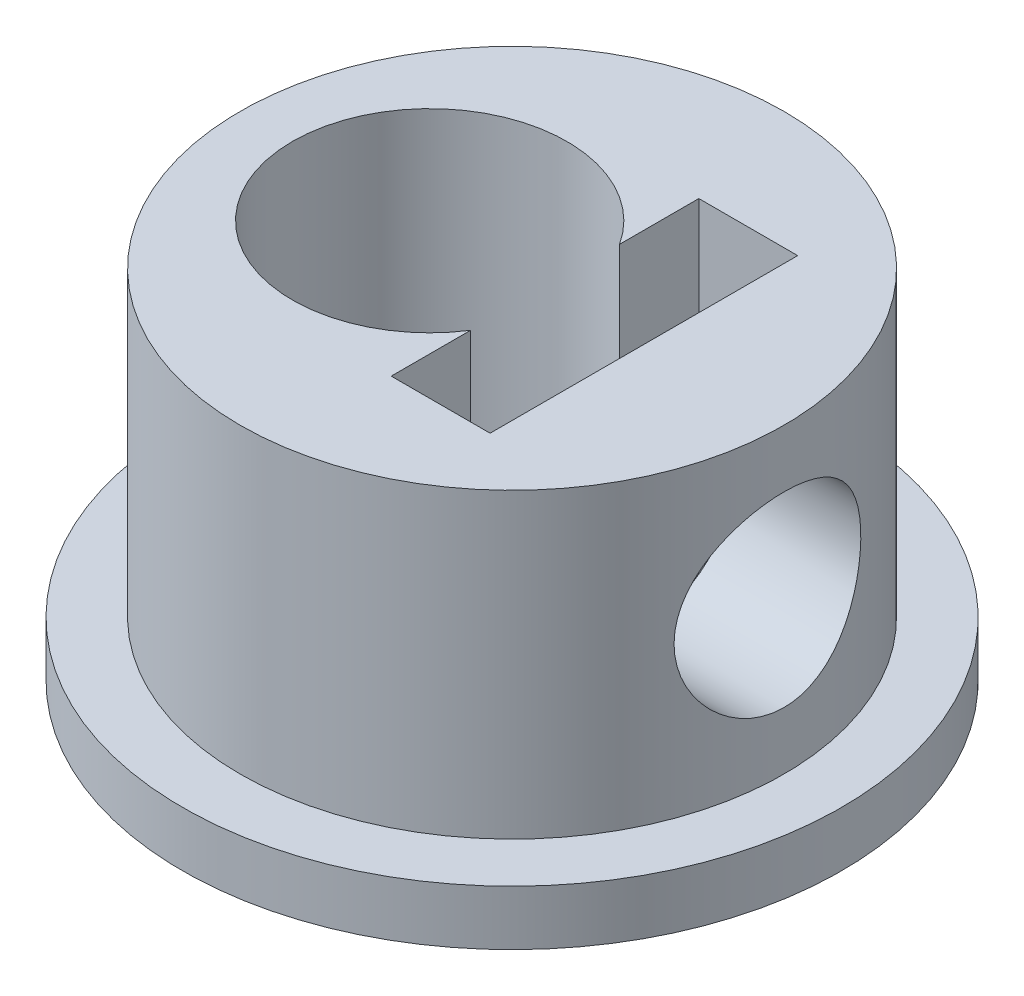
SolidWorks part; units mm, degrees
ref_plane "Front Plane" through (0, 0, 0) normal (0, 0, 1) x (1, 0, 0)
ref_plane "Top Plane" through (0, 0, 0) normal (0, 1, 0) x (1, 0, 0)
ref_plane "Right Plane" through (0, 0, 0) normal (1, 0, 0) x (0, 0, -1)
sketch "Sketch1" plane through (0, 0, 0) normal (0, 1, 0) x (1, 0, 0)
  circle A0 centre (0, 0) radius 2.5
  circle A1 centre (0, 0) radius 2.55 construction
  dimension "D1" = 5
  dimension "D2" = 5.1
extrude "Boss-Extrude1" add sketch "Sketch1" along normal blind 15
sketch "Sketch2" plane through (0, 15, 0) normal (0, 1, 0) x (1, 0, 0)
  circle A0 centre (1.5, 0) radius 4.95
  dimension "D1" = 9.9
  dimension "D2" = 1.5
extrude "Boss-Extrude2" add sketch "Sketch2" along normal blind 5.5
sketch "Sketch3" plane through (0, 20.5, 0) normal (0, 1, 0) x (1, 0, 0)
  circle A2 centre (0, 0) radius 2.5 construction
  circle A3 centre (0, 0) radius 2.5
extrude "Boss-Extrude3" [suppressed] add sketch "Sketch3" along normal blind 6.5
sketch "Sketch4" [suppressed] plane through (0, 27, 0) normal (0, 1, 0) x (1, 0, 0)
  line L0 (-2.0842, 3.4141) -> (-1.5, 0)
  line L1 (-1.5, 0) -> (-2.0842, -3.4141)
  circle A0 centre (0, 0) radius 2.5 construction
  circle A1 centre (0, 0) radius 2.5 construction
  arc A2 (-2.0842, 3.4141) -> (-2.0842, -3.4141) centre (0, 0) ccw
  circle A3 centre (1.5, 0) radius 4.95 construction
  dimension "D1" = 1.5
extrude "Cut-Extrude1" [suppressed] cut sketch "Sketch4" against normal up to surface (6.5 mm away)
fillet "Fillet1" [suppressed] radius 1
sketch "Sketch6" plane through (0, 0, 0) normal (0, -1, 0) x (1, 0, 0)
  line L1 (-3.6662, 0) -> (-1.8331, -3.175)
  line L2 (-1.8331, -3.175) -> (1.8331, -3.175)
  line L3 (1.8331, -3.175) -> (3.6662, 0)
  line L4 (3.6662, 0) -> (1.8331, 3.175)
  line L5 (1.8331, 3.175) -> (-1.8331, 3.175)
  line L6 (-1.8331, 3.175) -> (-3.6662, 0)
  circle A0 centre (0, 0) radius 3.175 construction
  dimension "D1" = 6.35
extrude "Cut-Extrude2" [suppressed] cut sketch "Sketch6" against normal blind 6 flip side to cut
fillet "Fillet2" [suppressed] radius 0.5
sketch "Sketch7" plane through (0, 15, 0) normal (0, -1, 0) x (1, 0, 0)
  line L0 (2, 1.5) -> (2, -1.5) construction
  line L1 (2.1, 2.8) -> (3.9, 2.8)
  line L2 (2.1, 2.8) -> (2.1, -2.8)
  line L3 (2.1, -2.8) -> (3.9, -2.8)
  line L4 (3.9, 2.8) -> (3.9, -2.8)
  line L5 (2.1, 2.8) -> (3.9, -2.8) construction
  line L6 (2.1, -2.8) -> (3.9, 2.8) construction
  circle A0 centre (1.5, 0) radius 4.95 construction
  circle A1 centre (0, 0) radius 2.5 construction
  circle A2 centre (1.5, 0) radius 4.95 construction
  circle A3 centre (0, 0) radius 2.5 construction
  point P6 (3, 0)
  dimension "D1" = 3.95
  dimension "D2" = 1.8
  dimension "D3" = 5.6
  dimension "D4" = 4.5
  dimension "D5" = 0.2
extrude "Cut-Extrude3" cut sketch "Sketch7" against normal up to surface (5.5 mm away) up to face at (1.5, 20.5, 4.95)
sketch "Sketch10" plane through (0, 0, 0) normal (0, -1, 0) x (1, 0, 0)
  circle A1 centre (0, 0) radius 2.5
  circle A2 centre (0, 0) radius 2.5
  dimension "D1" = 0
extrude "Cut-Extrude4" cut sketch "Sketch10" against normal through all
sketch "Sketch11" plane through (3.9, 0, 0) normal (-1, 0, 0) x (0, 0, 1)
  line L0 (-2.8, 20.5) -> (2.8, 15)
hole_wizard "M3 Clearance Hole1" positions "Sketch12" profile "Sketch13" hole size "M3" standard "ISO"
sketch "Sketch12" plane through (3.9, 0, 0) normal (-1, 0, 0) x (0, 0, 1)
  line L0 (-2.8, 20.5) -> (2.8, 15) construction
  point P0 (0, 17.75)
sketch "Sketch13" plane through (3.9, 17.75, 0) normal (0, 1, 0) x (0, 0, 1)
  line L0 (0, 0) -> (0, 2.55)
  line L1 (0, 2.55) -> (1.7, 2.55)
  line L2 (1.7, 2.55) -> (1.7, 0)
  line L5 (1.7, 0) -> (0, 0)
  line L11 (0, -6.35) -> (0, 107.95) construction
  dimension "Thru Hole Dia." = 3.4
  dimension "Thru Hole Depth" = 2.55
sketch "Sketch14" plane through (0, 15, 0) normal (0, -1, 0) x (1, 0, 0)
  line L5 (2.1, 2.8) -> (2.1, 1.3565)
  line L6 (3.9, 2.8) -> (2.1, 2.8)
  line L7 (3.9, -2.8) -> (3.9, 2.8)
  line L8 (2.1, -2.8) -> (3.9, -2.8)
  line L9 (2.1, -1.3565) -> (2.1, -2.8)
  line L10 (2.1, 2.8) -> (2.1, 1.3565)
  line L11 (3.9, 2.8) -> (2.1, 2.8)
  line L12 (3.9, -2.8) -> (3.9, 2.8)
  line L13 (2.1, -2.8) -> (3.9, -2.8)
  line L14 (2.1, -1.3565) -> (2.1, -2.8)
  circle A2 centre (1.5, 0) radius 6
  circle A3 centre (1.5, 0) radius 4.95 construction
  arc A6 (2.1, 1.3565) -> (2.1, -1.3565) centre (0, 0) ccw
  arc A7 (2.1, 1.3565) -> (2.1, -1.3565) centre (0, 0) ccw
  dimension "D1" = 12
  dimension "D2" = 0
extrude "Boss-Extrude5" add sketch "Sketch14" along normal blind 1
